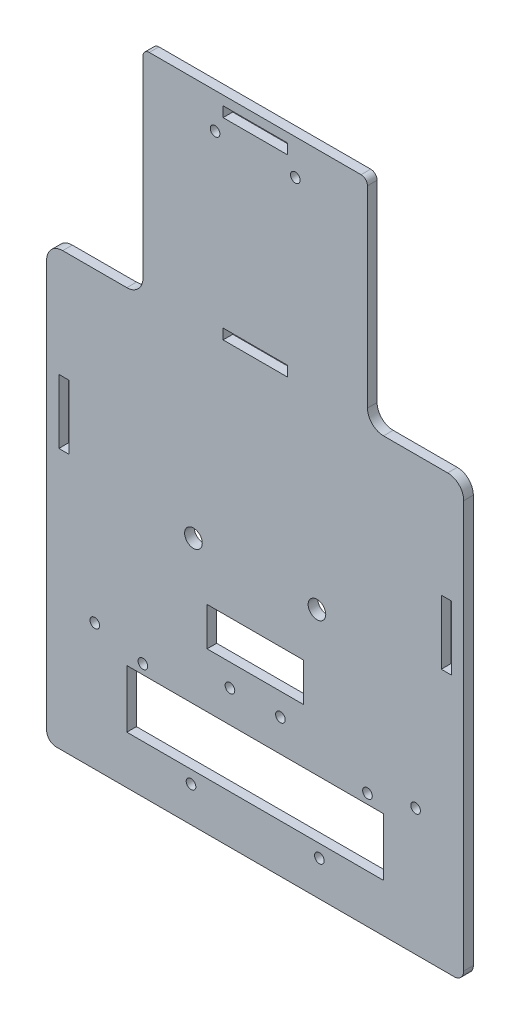
SolidWorks part; units mm, degrees
material "Maple"
ref_plane "Front Plane" through (0, 0, 0) normal (0, 0, 1) x (1, 0, 0)
ref_plane "Top Plane" through (0, 0, 0) normal (0, 1, 0) x (1, 0, 0)
ref_plane "Right Plane" through (0, 0, 0) normal (1, 0, 0) x (0, 0, -1)
sketch "Sketch1" plane through (0, 0, 0) normal (0, 0, 1) x (1, 0, 0)
  line L0 (-35, 117.25) -> (-35, 57.25)
  line L1 (-40, 52.25) -> (-60, 52.25)
  line L5 (-62, -82.75) -> (62, -82.75)
  line L9 (60, 52.25) -> (40, 52.25)
  line L10 (35, 57.25) -> (35, 117.25)
  line L12 (-65, 0) -> (65, 0) construction
  line L29 (61.2, 18.25) -> (58, 18.25)
  line L30 (61.2, 18.25) -> (61.2, -1.75)
  line L31 (61.2, -1.75) -> (58, -1.75)
  line L32 (58, 18.25) -> (58, -1.75)
  line L33 (61.2, 18.25) -> (58, -1.75) construction
  line L34 (61.2, -1.75) -> (58, 18.25) construction
  line L35 (-58, 18.25) -> (-61.2, 18.25)
  line L36 (-58, 18.25) -> (-58, -1.75)
  line L37 (-58, -1.75) -> (-61.2, -1.75)
  line L38 (-61.2, 18.25) -> (-61.2, -1.75)
  line L39 (-58, 18.25) -> (-61.2, -1.75) construction
  line L40 (-58, -1.75) -> (-61.2, 18.25) construction
  line L41 (-10, 56.35) -> (10, 56.35)
  line L42 (-10, 56.35) -> (-10, 53.15)
  line L43 (-10, 53.15) -> (10, 53.15)
  line L44 (10, 56.35) -> (10, 53.15)
  line L45 (-10, 56.35) -> (10, 53.15) construction
  line L46 (-10, 53.15) -> (10, 56.35) construction
  line L48 (-59.6, 8.25) -> (59.6, 8.25) construction
  line L49 (59.6, 8.25) -> (65, 8.25) construction
  line L50 (-59.6, 8.25) -> (-65, 8.25) construction
  line L52 (-20, -71.75) -> (20, -71.75) construction
  line L53 (-40, -49.75) -> (40, -49.75)
  line L54 (-40, -49.75) -> (-40, -67.75)
  line L55 (-40, -67.75) -> (40, -67.75)
  line L56 (40, -49.75) -> (40, -67.75)
  line L57 (-40, -49.75) -> (40, -67.75) construction
  line L58 (-40, -67.75) -> (40, -49.75) construction
  line L59 (35, -46.75) -> (-35, -46.75) construction
  line L60 (-7.865, -39.75) -> (7.865, -39.75) construction
  line L61 (-15, -20.75) -> (15, -20.75)
  line L62 (-15, -20.75) -> (-15, -32.75)
  line L63 (-15, -32.75) -> (15, -32.75)
  line L64 (15, -20.75) -> (15, -32.75)
  line L65 (-15, -20.75) -> (15, -32.75) construction
  line L66 (-15, -32.75) -> (15, -20.75) construction
  line L73 (-33, 119.25) -> (33, 119.25)
  line L75 (-10, 116.35) -> (10, 116.35)
  line L76 (-10, 116.35) -> (-10, 113.15)
  line L77 (-10, 113.15) -> (10, 113.15)
  line L78 (10, 116.35) -> (10, 113.15)
  line L79 (-10, 116.35) -> (10, 113.15) construction
  line L80 (-10, 113.15) -> (10, 116.35) construction
  line L88 (-35, 108.25) -> (-12.5, 108.25) construction
  line L93 (-12.5, 108.25) -> (12.5, 108.25) construction
  line L94 (12.5, 108.25) -> (35, 108.25) construction
  line L99 (-65, -43.25) -> (-50, -43.25) construction
  line L100 (-50, -43.25) -> (50, -43.25) construction
  line L101 (50, -43.25) -> (65, -43.25) construction
  line L103 (-65, -5) -> (-19.25, -5) construction
  line L104 (-19.25, -5) -> (19.25, -5) construction
  line L105 (19.25, -5) -> (65, -5) construction
  line L106 (65, 47.25) -> (65, -79.75)
  line L107 (-65, 47.25) -> (-65, -79.75)
  circle A14 centre (-20, -71.75) radius 1.5
  circle A15 centre (20, -71.75) radius 1.5
  circle A16 centre (-35, -46.75) radius 1.5
  circle A17 centre (35, -46.75) radius 1.5
  circle A18 centre (-7.865, -39.75) radius 1.5
  circle A19 centre (7.865, -39.75) radius 1.5
  arc A30 (35, 117.25) -> (33, 119.25) centre (33, 117.25) ccw
  arc A31 (-33, 119.25) -> (-35, 117.25) centre (-33, 117.25) ccw
  circle A32 centre (-19.25, -5) radius 2.75
  circle A33 centre (19.25, -5) radius 2.75
  arc A34 (65, -79.75) -> (62, -82.75) centre (62, -79.75) cw
  arc A35 (-62, -82.75) -> (-65, -79.75) centre (-62, -79.75) cw
  circle A36 centre (-50, -43.25) radius 1.5
  circle A37 centre (50, -43.25) radius 1.5
  circle A38 centre (-12.5, 108.25) radius 1.5
  circle A39 centre (12.5, 108.25) radius 1.5
  arc A40 (65, 47.25) -> (60, 52.25) centre (60, 47.25) ccw
  arc A41 (40, 52.25) -> (35, 57.25) centre (40, 57.25) cw
  arc A42 (-35, 57.25) -> (-40, 52.25) centre (-40, 57.25) cw
  arc A43 (-60, 52.25) -> (-65, 47.25) centre (-60, 47.25) ccw
  point P0 (0, 114.75)
  point P14 (0, 0)
  point P56 (59.6, 8.25)
  point P61 (-59.6, 8.25)
  point P66 (0, 54.75)
  point P79 (65, -16.25)
  point P88 (0, -58.75)
  point P96 (-35, -46.75)
  point P97 (0, -71.75)
  point P98 (-20, -71.75)
  point P103 (0, -39.75)
  point P104 (0, -46.75)
  point P105 (0, -26.75)
  point P139 (0, -82.75)
  dimension "D11" = 135
  dimension "D12" = 137.5
  dimension "D21" = 3
  dimension "D7" = 4.5
  dimension "D14" = 91
  dimension "D32" = 11
  dimension "D33" = 39.5
  dimension "D34" = 2
  dimension "D35" = 5.5
  dimension "D5" = 3
  dimension "D13" = 25
  dimension "D39" = 5
  dimension "D4" = 70
  dimension "D6" = 130
  dimension "D8" = 202
  dimension "D9" = 20
  dimension "D10" = 16.25
  dimension "D16" = 116
  dimension "D18" = 3.2
  dimension "D19" = 40
  dimension "D20" = 70
  dimension "D22" = 11
  dimension "D23" = 4
  dimension "D24" = 18
  dimension "D25" = 80
  dimension "D26" = 3
  dimension "D27" = 10
  dimension "D28" = 12
  dimension "D29" = 30
  dimension "D30" = 7
  dimension "D31" = 15.73
  dimension "D36" = 38.5
  dimension "D37" = 5
  dimension "D38" = 100
extrude "Boss-Extrude2" add sketch "Sketch1" along normal blind 3
